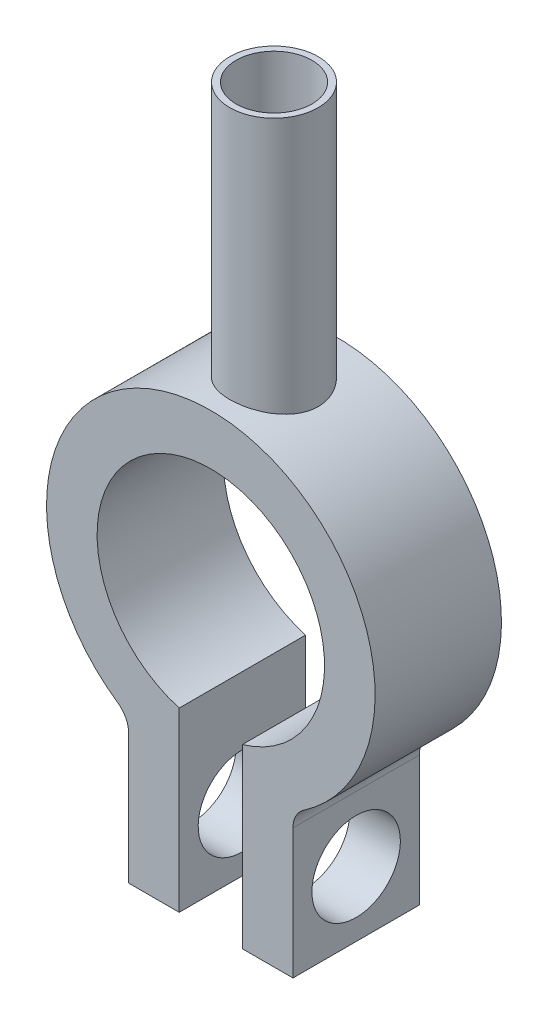
SolidWorks part; units mm, degrees
material "ABS generico"
ref_plane "Piano frontale" through (0, 0, 0) normal (0, 0, 1) x (1, 0, 0)
ref_plane "Piano superiore" through (0, 0, 0) normal (0, 1, 0) x (1, 0, 0)
ref_plane "Piano destro" through (0, 0, 0) normal (1, 0, 0) x (0, 0, -1)
sketch "Schizzo1" plane through (0, 0, 0) normal (0, 0, 1) x (1, 0, 0)
  circle A0 centre (0, 0) radius 9
  circle A1 centre (0, 0) radius 13
  dimension "D1" = 18
  dimension "D2" = 26
extrude "Anello" add sketch "Schizzo1" along normal blind 10
sketch "Schizzo2" plane through (0, 0, 10) normal (0, 0, 1) x (1, 0, 0)
  line L1 (-2.5, 0) -> (2.5, 0)
  line L2 (-2.5, 0) -> (-2.5, -13)
  line L3 (-2.5, -13) -> (2.5, -13)
  line L4 (2.5, 0) -> (2.5, -13)
  circle A0 centre (0, 0) radius 13 construction
  point P4 (0, 0)
  dimension "D1" = 5
extrude "TaglioAnello" cut sketch "Schizzo2" against normal through all
sketch "Schizzo3" plane through (0, 0, 10) normal (0, 0, 1) x (1, 0, 0)
  line L1 (-2.5, -8.6458) -> (-6.5, -8.6458)
  line L2 (-2.5, -8.6458) -> (-2.5, -22.6458)
  line L3 (-2.5, -22.6458) -> (-6.5, -22.6458)
  line L4 (-6.5, -8.6458) -> (-6.5, -22.6458)
  dimension "D1" = 4
  dimension "D2" = 14
extrude "BordoViteDestro" add sketch "Schizzo3" against normal up to surface (10 mm away) up to face at (0, 0.1492, 0)
mirror "BordoViteSinistro" about plane through (0, 0, 0) normal (1, 0, 0) of "BordoViteDestro"
fillet "RaccordoDestro" radius 2 1 edges at (-6.5, -11.2583, 5)
fillet "RaccordoSinistro" radius 2 1 edges at (6.5, -11.2583, 5)
sketch "Schizzo4" plane through (6.5, 0, 0) normal (1, 0, 0) x (0, 0, -1)
  line L0 (0, -22.6458) -> (-10, -22.6458) construction
  line L1 (-10, -12.3592) -> (-10, -22.6458) construction
  circle A0 centre (-5, -17.5025) radius 3.5
  point P5 (-5, -22.6458)
  point P8 (-10, -17.5025)
  dimension "D1" = 7
extrude "ForoVite" cut sketch "Schizzo4" against normal through all
ref_plane "PianoTangenteSuperiore" through (0, 13, 0) normal (0, 1, 0) x (1, 0, 0)
sketch "Schizzo5" plane through (0, 13, 0) normal (0, 1, 0) x (1, 0, 0)
  line L0 (-13, 0) -> (-13, -10) construction
  line L1 (-13, 0) -> (13, 0) construction
  line L2 (-13, 0) -> (-13, -10) construction
  line L3 (-13, -10) -> (13, -10) construction
  line L4 (13, 0) -> (13, -10) construction
  line L5 (-13, -10) -> (13, -10) construction
  line L6 (13, 0) -> (-13, 0) construction
  line L7 (-13, 0) -> (13, -10) construction
  line L8 (-13, -10) -> (13, 0) construction
  circle A0 centre (0, -5) radius 3
  circle A1 centre (0, -5) radius 3.5
  dimension "D1" = 6
  dimension "D2" = 7
  dimension "D3" = 26
extrude "AggancioLongheroneCoda" add sketch "Schizzo5" along normal blind 20 and the other way blind 2 separate body
